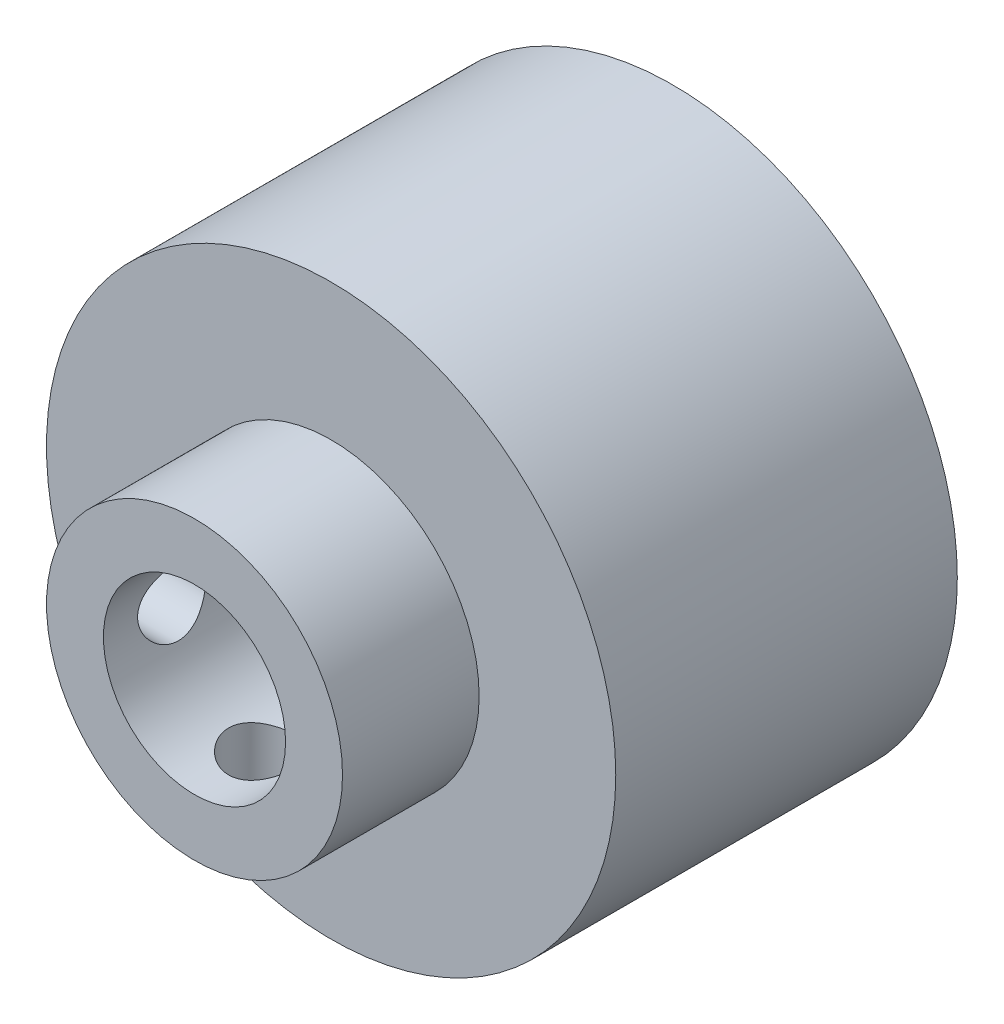
SolidWorks part; units mm, degrees
ref_plane "Front Plane" through (0, 0, 0) normal (0, 0, 1) x (1, 0, 0)
ref_plane "Top Plane" through (0, 0, 0) normal (0, 1, 0) x (1, 0, 0)
ref_plane "Right Plane" through (0, 0, 0) normal (1, 0, 0) x (0, 0, -1)
sketch "Sketch1" plane through (0, 0, 0) normal (0, 0, 1) x (1, 0, 0)
  circle A0 centre (0, 0) radius 12.5
  dimension "D1" = 25
extrude "Boss-Extrude1" add sketch "Sketch1" along normal blind 15
sketch "Sketch2" plane through (0, 0, 15) normal (0, 0, 1) x (1, 0, 0)
  circle A0 centre (0, 0) radius 6.5
  dimension "D1" = 13
extrude "Boss-Extrude2" add sketch "Sketch2" along normal blind 6
sketch "Sketch3" plane through (0, 0, 21) normal (0, 0, 1) x (1, 0, 0)
  circle A0 centre (0, 0) radius 4
  dimension "D1" = 8
extrude "Cut-Extrude1" cut sketch "Sketch3" against normal through all
sketch "Sketch4" plane through (0, 0, 0) normal (0, 1, 0) x (1, 0, 0)
  line L0 (-6.5, -15) -> (-6.5, -21) construction
  circle A0 centre (0, -18) radius 1.5
  point P4 (-6.5, -18)
  dimension "D1" = 3
extrude "Cut-Extrude2" cut sketch "Sketch4" against normal through all
sketch "Sketch5" plane through (0, 0, 0) normal (1, 0, 0) x (0, 0, -1)
  line L0 (-15, 6.5) -> (-21, 6.5) construction
  circle A0 centre (-18, 0) radius 1.5
  point P4 (-18, 6.5)
  dimension "D1" = 3
extrude "Cut-Extrude3" cut sketch "Sketch5" against normal through all
